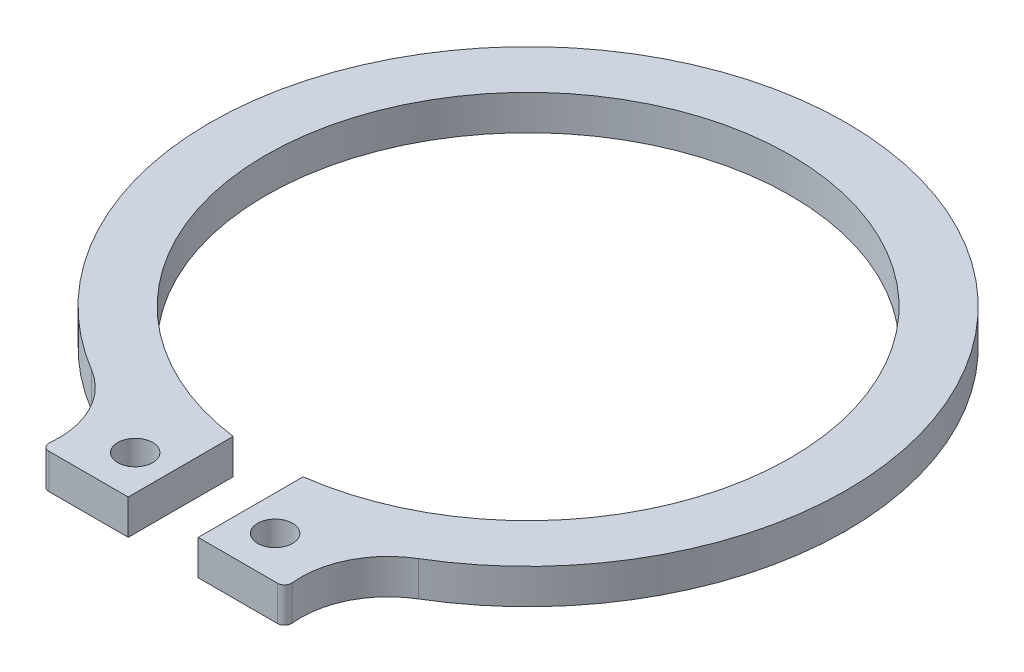
SolidWorks part; units mm, degrees
material "Plain Carbon Steel"
ref_plane "Front Plane" through (0, 0, 0) normal (0, 0, 1) x (1, 0, 0)
ref_plane "Top Plane" through (0, 0, 0) normal (0, 1, 0) x (1, 0, 0)
ref_plane "Right Plane" through (0, 0, 0) normal (1, 0, 0) x (0, 0, -1)
sketch "Sketch1" plane through (0, 0, 0) normal (0, 1, 0) x (1, 0, 0)
  line L0 (-1.27, -9.44) -> (-1.27, -13.25)
  line L1 (1.27, -9.44) -> (1.27, -13.25)
  line L2 (0, -12.065) -> (0, 0) construction
  line L3 (1.27, -13.25) -> (4.445, -13.25)
  line L4 (-1.27, -13.25) -> (-4.445, -13.25)
  arc A0 (1.27, -9.44) -> (-1.27, -9.44) centre (0, 0) ccw
  arc A1 (5.9319, -9.9185) -> (-5.9319, -9.9185) centre (0, 0) ccw
  arc A2 (4.445, -13.25) -> (5.9319, -9.9185) centre (7.5615, -12.6434) cw
  arc A3 (-4.445, -13.25) -> (-5.9319, -9.9185) centre (-7.5615, -12.6434) ccw
  circle A4 centre (-2.54, -11.726) radius 0.635
  circle A5 centre (2.54, -11.726) radius 0.635
  dimension "D1" = 19.05
  dimension "D3" = 2.032
  dimension "D6" = 3.175
  dimension "D2" = 1.27
  dimension "D4" = 1.27
  dimension "D5" = 3.81
  dimension "D7" = 3.175
  dimension "D8" = 1.524
  dimension "D9" = 1.27
extrude "Boss-Extrude1" add sketch "Sketch1" along normal blind 1.27 contours A3 L4 L0 A0 L1 L3 A2 A1 A5 A4
fillet "Fillet1" radius 0.254 2 edges at (4.445, 0.635, 13.25) (-4.445, 0.635, 13.25)
